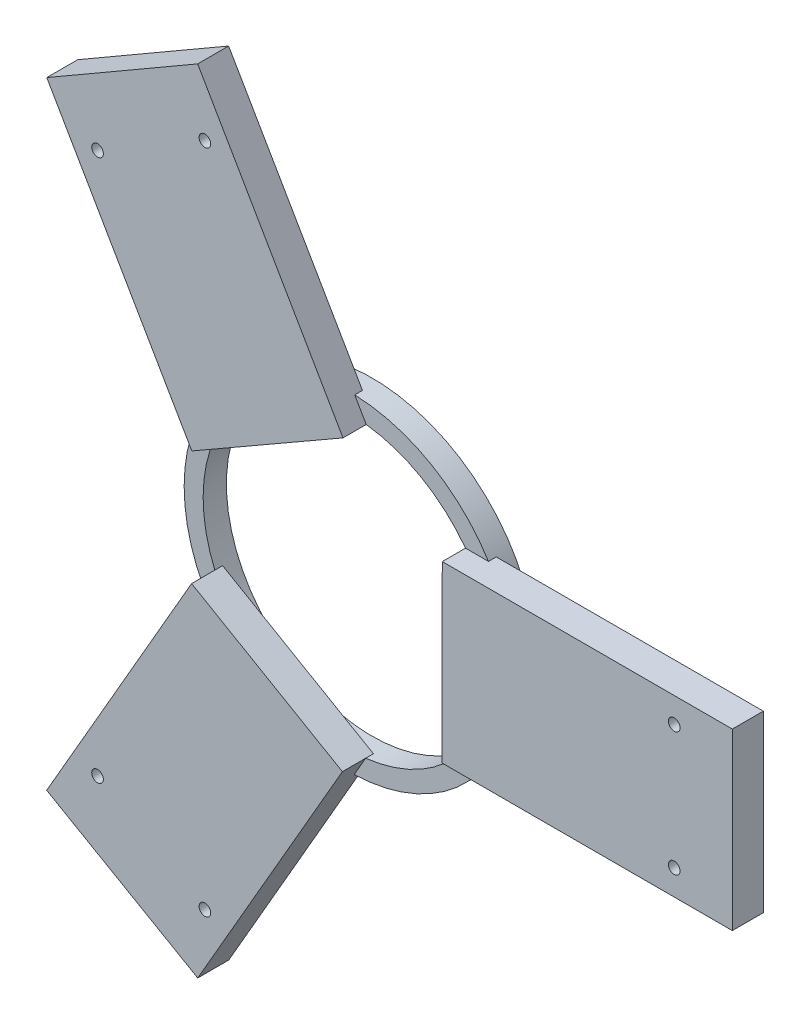
SolidWorks part; units mm, degrees
ref_plane "Front Plane" through (0, 0, 0) normal (0, 0, 1) x (1, 0, 0)
ref_plane "Top Plane" through (0, 0, 0) normal (0, 1, 0) x (1, 0, 0)
ref_plane "Right Plane" through (0, 0, 0) normal (1, 0, 0) x (0, 0, -1)
sketch "Sketch1" plane through (0, 0, 0) normal (0, 0, 1) x (1, 0, 0)
  circle A0 centre (300, 300) radius 85
extrude "Boss-Extrude1" add sketch "Sketch1" along normal blind 12
sketch "Sketch2" plane through (0, 0, 12) normal (0, 0, 1) x (1, 0, 0)
  circle A0 centre (300, 300) radius 75.2
extrude "Cut-Extrude1" cut sketch "Sketch2" against normal blind 32
ref_plane "Plane1" through (0, 0, 8) normal (0, 0, 1) x (1, 0, 0)
sketch "Sketch3" plane through (0, 0, 8) normal (0, 0, 1) x (1, 0, 0)
  line L0 (360.16, 254.88) -> (510, 254.88)
  line L1 (510, 254.88) -> (510, 345)
  line L2 (510, 345) -> (360.2498, 345)
  line L3 (360.2498, 345) -> (360.16, 254.88)
  circle A0 centre (300, 300) radius 75.2 construction
extrude "Boss-Extrude2" add sketch "Sketch3" along normal blind 16
sketch "Sketch4" plane through (0, 0, 24) normal (0, 0, 1) x (1, 0, 0)
  circle A0 centre (480, 268) radius 3
extrude "Cut-Extrude2" cut sketch "Sketch4" against normal blind 44
sketch "Sketch5" plane through (0, 0, 24) normal (0, 0, 1) x (1, 0, 0)
  circle A0 centre (480, 332) radius 3
extrude "Cut-Extrude3" cut sketch "Sketch5" against normal blind 44
ref_plane "Plane2" through (0, 0, 8) normal (0, 0, 1) x (1, 0, 0)
sketch "Sketch6" plane through (0, 0, 8) normal (0, 0, 1) x (1, 0, 0)
  line L0 (308.9951, 374.6601) -> (233.9711, 504.3653)
  line L1 (233.9711, 504.3653) -> (156.0649, 459.3029)
  line L2 (156.0649, 459.3029) -> (230.9631, 329.8152)
  line L3 (230.9631, 329.8152) -> (308.9951, 374.6601)
  arc A0 (360.2498, 345) -> (360.16, 254.88) centre (300, 300) ccw construction
extrude "Boss-Extrude3" add sketch "Sketch6" along normal blind 16
sketch "Sketch7" plane through (0, 0, 24) normal (0, 0, 1) x (1, 0, 0)
  circle A0 centre (237.7128, 471.8846) radius 3
extrude "Cut-Extrude4" cut sketch "Sketch7" against normal blind 44
sketch "Sketch8" plane through (0, 0, 24) normal (0, 0, 1) x (1, 0, 0)
  circle A0 centre (182.2872, 439.8846) radius 3
extrude "Cut-Extrude5" cut sketch "Sketch8" against normal blind 44
ref_plane "Plane3" through (0, 0, 8) normal (0, 0, 1) x (1, 0, 0)
sketch "Sketch9" plane through (0, 0, 8) normal (0, 0, 1) x (1, 0, 0)
  line L0 (230.8449, 270.4599) -> (156.0289, 140.6347)
  line L1 (156.0289, 140.6347) -> (234.0071, 95.6971)
  line L2 (234.0071, 95.6971) -> (308.6978, 225.3047)
  line L3 (308.6978, 225.3047) -> (230.8449, 270.4599)
  arc A0 (230.9631, 329.8152) -> (360.16, 254.88) centre (300, 300) ccw construction
extrude "Boss-Extrude4" add sketch "Sketch9" along normal blind 16
sketch "Sketch10" plane through (0, 0, 24) normal (0, 0, 1) x (1, 0, 0)
  circle A0 centre (182.2872, 160.1154) radius 3
extrude "Cut-Extrude6" cut sketch "Sketch10" against normal blind 44
sketch "Sketch11" plane through (0, 0, 24) normal (0, 0, 1) x (1, 0, 0)
  circle A0 centre (237.7128, 128.1154) radius 3
extrude "Cut-Extrude7" cut sketch "Sketch11" against normal blind 44
